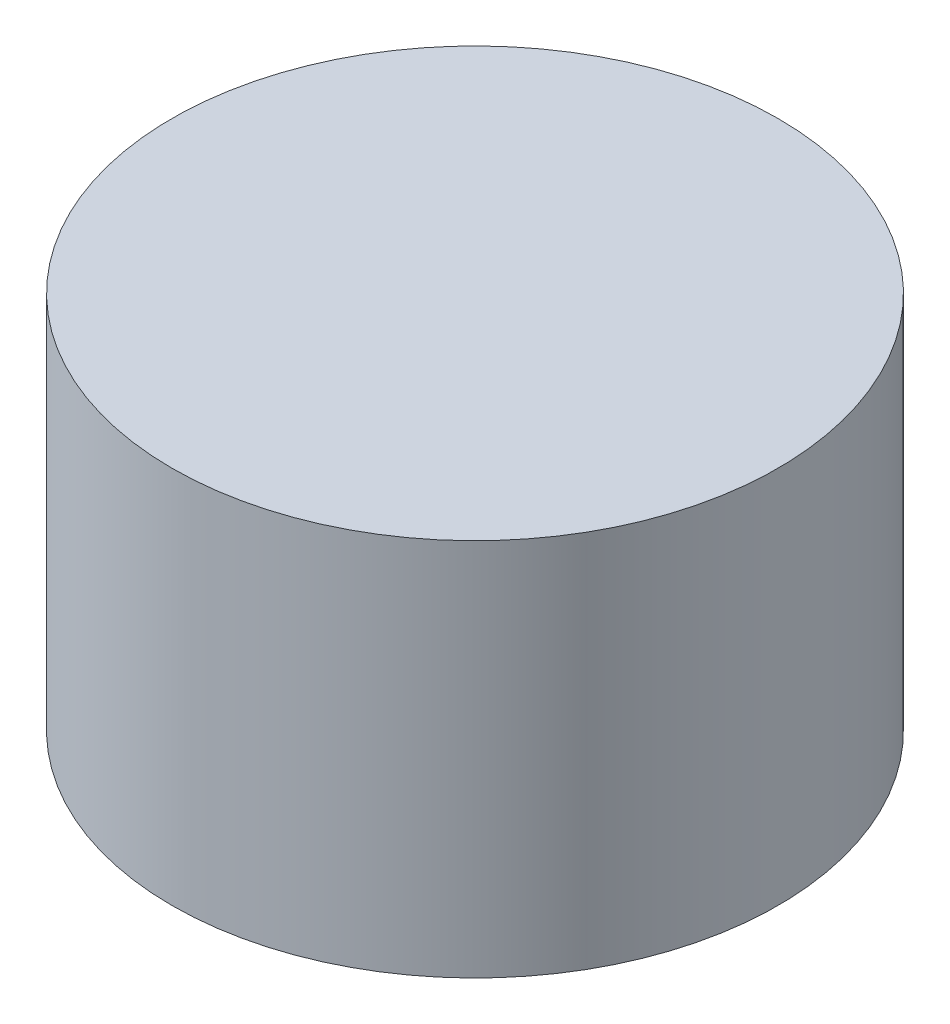
SolidWorks part; units mm, degrees
ref_plane "Front Plane" through (0, 0, 0) normal (0, 0, 1) x (1, 0, 0)
ref_plane "Top Plane" through (0, 0, 0) normal (0, 1, 0) x (1, 0, 0)
ref_plane "Right Plane" through (0, 0, 0) normal (1, 0, 0) x (0, 0, -1)
sketch "Sketch2" plane through (0, 0, 0) normal (0, 1, 0) x (1, 0, 0)
  circle A0 centre (0, 0) radius 16
  dimension "D1" = 32
extrude "Boss-Extrude1" add sketch "Sketch2" along normal blind 20
sketch "Sketch3" plane through (0, 20, 0) normal (0, 1, 0) x (1, 0, 0)
  circle A0 centre (0, 0) radius 15
  dimension "D1" = 30
extrude "Cut-Extrude1" cut sketch "Sketch3" against normal through all from offset 2 offset against normal yes
sketch "Sketch4" plane through (0, 18, 0) normal (0, -1, 0) x (-1, 0, 0)
  circle A0 centre (0, 0) radius 3
  dimension "D1" = 6
extrude "Boss-Extrude2" add sketch "Sketch4" along normal blind 1
